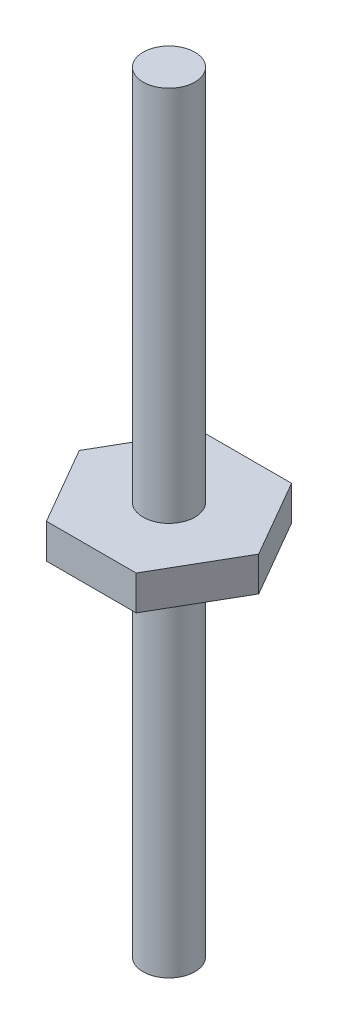
SolidWorks part; units mm, degrees
ref_plane "Front Plane" through (0, 0, 0) normal (0, 0, 1) x (1, 0, 0)
ref_plane "Top Plane" through (0, 0, 0) normal (0, 1, 0) x (1, 0, 0)
ref_plane "Right Plane" through (0, 0, 0) normal (1, 0, 0) x (0, 0, -1)
sketch "Sketch1" plane through (0, 0, 0) normal (0, 1, 0) x (1, 0, 0)
  circle A0 centre (0, 0) radius 1.5
  dimension "D1" = 3
extrude "Boss-Extrude1" add sketch "Sketch1" along normal blind 23.825
ref_plane "Plane1" through (0, 23.825, 0) normal (0, 1, 0) x (1, 0, 0)
ref_point "Point1"
sketch "Sketch2" plane through (0, 23.825, 0) normal (0, 1, 0) x (1, 0, 0)
  circle A0 centre (0, 0) radius 1
  dimension "D1" = 2
ref_plane "Plane2" through (0, 0, 0) normal (0, -1, 0) x (-1, 0, 0)
sketch "Sketch3" plane through (0, 0, 0) normal (0, -1, 0) x (-1, 0, 0)
  line L1 (5.1962, 0) -> (2.5981, 4.5)
  line L2 (2.5981, 4.5) -> (-2.5981, 4.5)
  line L3 (-2.5981, 4.5) -> (-5.1962, 0)
  line L4 (-5.1962, 0) -> (-2.5981, -4.5)
  line L5 (-2.5981, -4.5) -> (2.5981, -4.5)
  line L6 (2.5981, -4.5) -> (5.1962, 0)
  circle A0 centre (0, 0) radius 4.5 construction
extrude "Boss-Extrude2" add sketch "Sketch3" against normal blind 2
sketch "Sketch4" plane through (0, 0, 0) normal (0, -1, 0) x (-1, 0, 0)
  circle A0 centre (0, 0) radius 1.5
  dimension "D1" = 3
extrude "Boss-Extrude3" add sketch "Sketch4" along normal blind 20.8
ref_plane "Plane3" through (1.5, 0, 0) normal (1, 0, 0) x (0, 0, -1)
sketch "Sketch5" plane through (0, 23.825, 0) normal (0, 1, 0) x (1, 0, 0)
